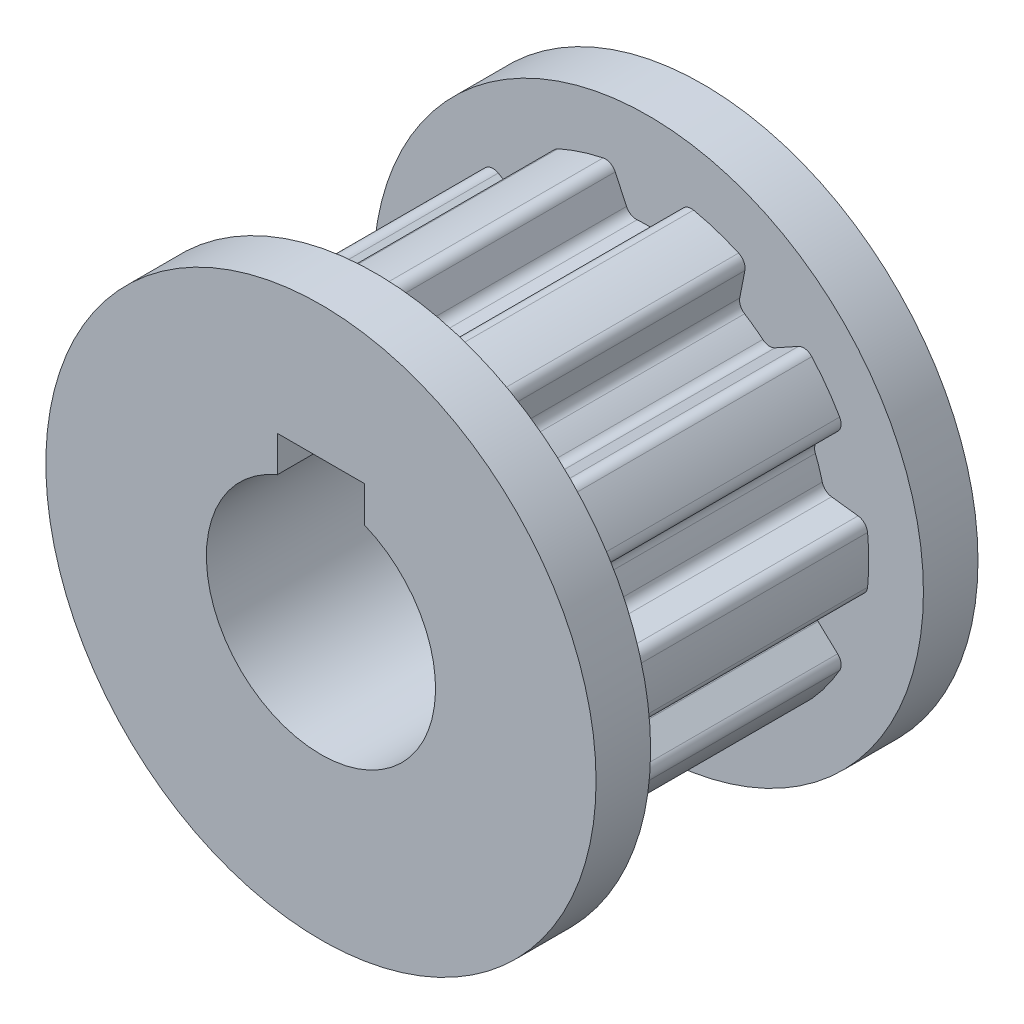
SolidWorks part; units mm, degrees
ref_plane "Front Plane" through (0, 0, 0) normal (0, 0, 1) x (1, 0, 0)
ref_plane "Top Plane" through (0, 0, 0) normal (0, 1, 0) x (1, 0, 0)
ref_plane "Right Plane" through (0, 0, 0) normal (1, 0, 0) x (0, 0, -1)
sketch "Sketch1" plane through (0, 0, 0) normal (0, 1, 0) x (1, 0, 0)
  line L0 (0, 0) -> (0, 21.1203) construction
  line L3 (0, 14) -> (-10.0851, 14)
  line L4 (-10.0851, 14) -> (-10.0851, 12)
  line L5 (-10.0851, 12) -> (-8.0851, 12)
  line L6 (-8.0851, 12) -> (-8.0851, 2)
  line L7 (-8.0851, 2) -> (-10.0851, 2)
  line L8 (-10.0851, 2) -> (-10.0851, 0)
  line L9 (-10.0851, 0) -> (0, 0)
  line L10 (0, 0) -> (0, 14)
  line L11 (-10.0851, 12) -> (-10.0851, 2) construction
  dimension "D1" = 8.0851
  dimension "D2" = 2
  dimension "D3" = 10
  dimension "D4" = 2
  dimension "D5" = 2
revolve "Revolve1" add sketch "Sketch1" angle 360 about L10
ref_plane "Plane1" through (0, 0, -7) normal (0, 0, 1) x (1, 0, 0)
sketch "Sketch6" plane through (0, 0, -7) normal (0, 0, 1) x (1, 0, 0)
  line L0 (0, 0) -> (0, 10.2344) construction
  line L1 (-0.7984, 6.8024) -> (-1.2127, 7.6909)
  line L2 (0.7984, 6.8024) -> (1.2127, 7.6909)
  arc A0 (0.4109, 6.5722) -> (-0.4109, 6.5722) centre (0, 0) ccw
  arc A1 (-0.4109, 6.5722) -> (-0.7984, 6.8024) centre (-0.4359, 6.9715) cw
  arc A2 (0.4109, 6.5722) -> (0.7984, 6.8024) centre (0.4359, 6.9715) ccw
  arc A3 (-1.2127, 7.6909) -> (-1.6573, 7.9134) centre (-1.5753, 7.5219) ccw
  arc A4 (1.2127, 7.6909) -> (1.6573, 7.9134) centre (1.5753, 7.5219) cw
  arc A5 (-1.6573, 7.9134) -> (1.6573, 7.9134) centre (0, 0) cw
  circle A6 centre (0, 0) radius 8.0851 construction
  arc A7 (0.7833, 6.7699) -> (-0.7833, 6.7699) centre (0, 0) ccw construction
  point P15 (0, 6.5851)
  point P20 (0, 8.0851)
  dimension "D2" = 0.4
  dimension "D3" = 0.4
  dimension "D4" = 1.5
  dimension "D5" = 1.27
  dimension "D6" = 1.57
  dimension "D1" = 50
extrude "Cut-Extrude4" cut sketch "Sketch6" against normal up to surface and the other way up to surface up to face at (8.0851, 0, -12) other way up to face at (10.0851, 0, -2)
pattern_circular "CirPattern1" count 10 over 360 about axis through (0, 0, 0) along (0, 0, 1) of "Cut-Extrude4"
sketch "Sketch2" plane through (0, 0, 0) normal (0, 0, 1) x (1, 0, 0)
  circle A0 centre (0, 0) radius 4.2
  circle A1 centre (0, 0) radius 10.0851 construction
  dimension "D1" = 8.4
extrude "Cut-Extrude1" cut sketch "Sketch2" against normal through all
sketch "Sketch7" plane through (0, 0, 0) normal (0, 0, 1) x (1, 0, 0)
  line L1 (-1.6, 5.2) -> (1.6, 5.2)
  line L2 (-1.6, 5.2) -> (-1.6, 0)
  line L3 (-1.6, 0) -> (1.6, 0)
  line L4 (1.6, 5.2) -> (1.6, 0)
  circle A2 centre (0, 0) radius 4.2 construction
  point P4 (0, 0)
  dimension "D1" = 3.2
  dimension "D2" = 1
extrude "Cut-Extrude5" cut sketch "Sketch7" against normal through all
sketch "Sketch3" plane through (0, 0, 0) normal (0, 1, 0) x (1, 0, 0)
  line L2 (-11.0936, 7) -> (11.0936, 7) construction
  circle A0 centre (0, 7) radius 1.25
  dimension "D2" = 2.5
extrude "Cut-Extrude2" cut sketch "Sketch3" against normal through all
sketch "Sketch4" plane through (0, 0, 0) normal (1, 0, 0) x (0, 0, -1)
  line L2 (7, 11.0936) -> (7, -11.0936) construction
  circle A0 centre (7, 0) radius 1.25
  dimension "D2" = 2.5
extrude "Cut-Extrude3" cut sketch "Sketch4" against normal through all
equation "\"teeth\"= 10"
equation "\"pitch\"= 0.2in"
equation "\"pitch diameter\"= \"teeth\" * \"pitch\" / pi"
equation "\"D1@Sketch1\"=\"pitch diameter\"/2"
equation "\"D1@CirPattern1\"=\"teeth\""
